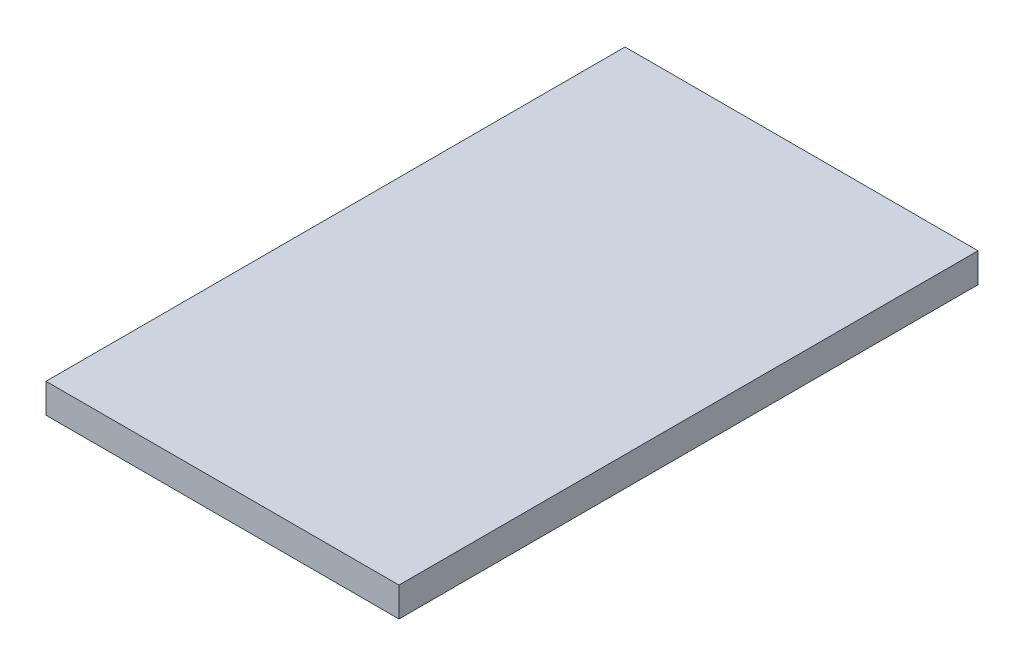
SolidWorks part; units mm, degrees
ref_plane "Front Plane" through (0, 0, 0) normal (0, 0, 1) x (1, 0, 0)
ref_plane "Top Plane" through (0, 0, 0) normal (0, 1, 0) x (1, 0, 0)
ref_plane "Right Plane" through (0, 0, 0) normal (1, 0, 0) x (0, 0, -1)
sketch "Sketch1" plane through (0, 0, 0) normal (0, 1, 0) x (1, 0, 0)
  line L1 (-7.62, 12.5) -> (7.62, 12.5)
  line L2 (-7.62, 12.5) -> (-7.62, -12.5)
  line L3 (-7.62, -12.5) -> (7.62, -12.5)
  line L4 (7.62, 12.5) -> (7.62, -12.5)
  line L5 (-7.62, 12.5) -> (7.62, -12.5) construction
  line L6 (-7.62, -12.5) -> (7.62, 12.5) construction
  point P0 (0, 0)
  dimension "D1" = 15.24
  dimension "D2" = 25
extrude "Boss-Extrude1" add sketch "Sketch1" along normal mid plane 1.27
